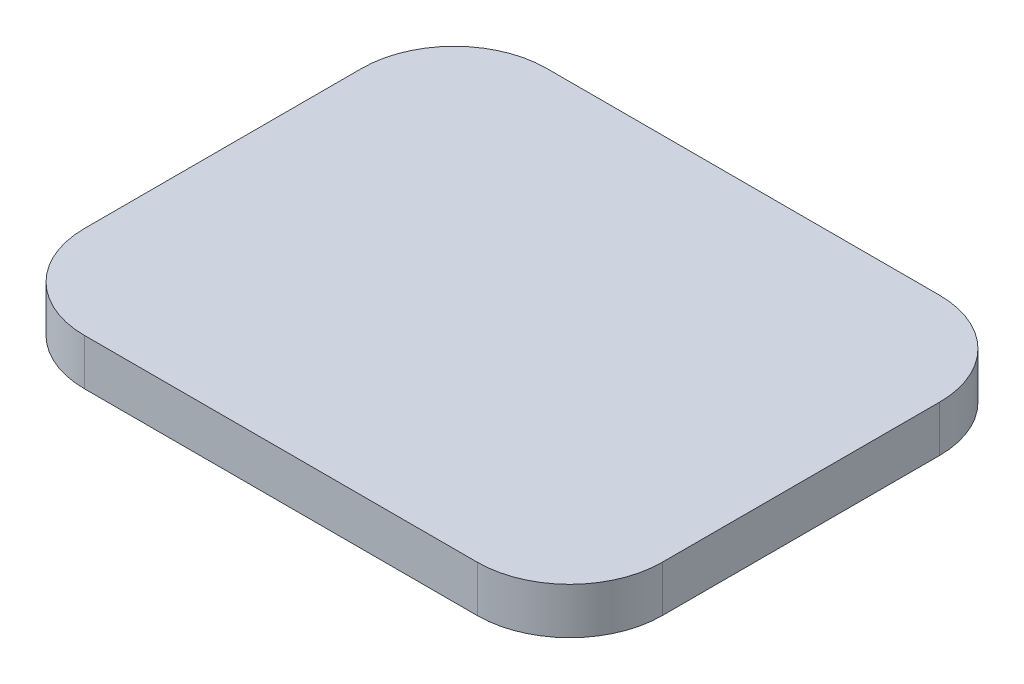
SolidWorks part; units mm, degrees
ref_plane "Front Plane" through (0, 0, 0) normal (0, 0, 1) x (1, 0, 0)
ref_plane "Top Plane" through (0, 0, 0) normal (0, 1, 0) x (1, 0, 0)
ref_plane "Right Plane" through (0, 0, 0) normal (1, 0, 0) x (0, 0, -1)
sketch "Sketch1" plane through (0, 0, 0) normal (0, 1, 0) x (1, 0, 0)
  line L1 (-12.5, 10) -> (12.5, 10)
  line L2 (-12.5, 10) -> (-12.5, -10)
  line L3 (-12.5, -10) -> (12.5, -10)
  line L4 (12.5, 10) -> (12.5, -10)
  line L5 (-12.5, 10) -> (12.5, -10) construction
  line L6 (-12.5, -10) -> (12.5, 10) construction
  point P0 (0, 0)
  dimension "D1" = 25
  dimension "D2" = 20
extrude "Boss-Extrude1" add sketch "Sketch1" along normal blind 2
fillet "Fillet1" radius 4 4 edges at (-12.5, 1, -10) (12.5, 1, -10) (12.5, 1, 10) (-12.5, 1, 10)
